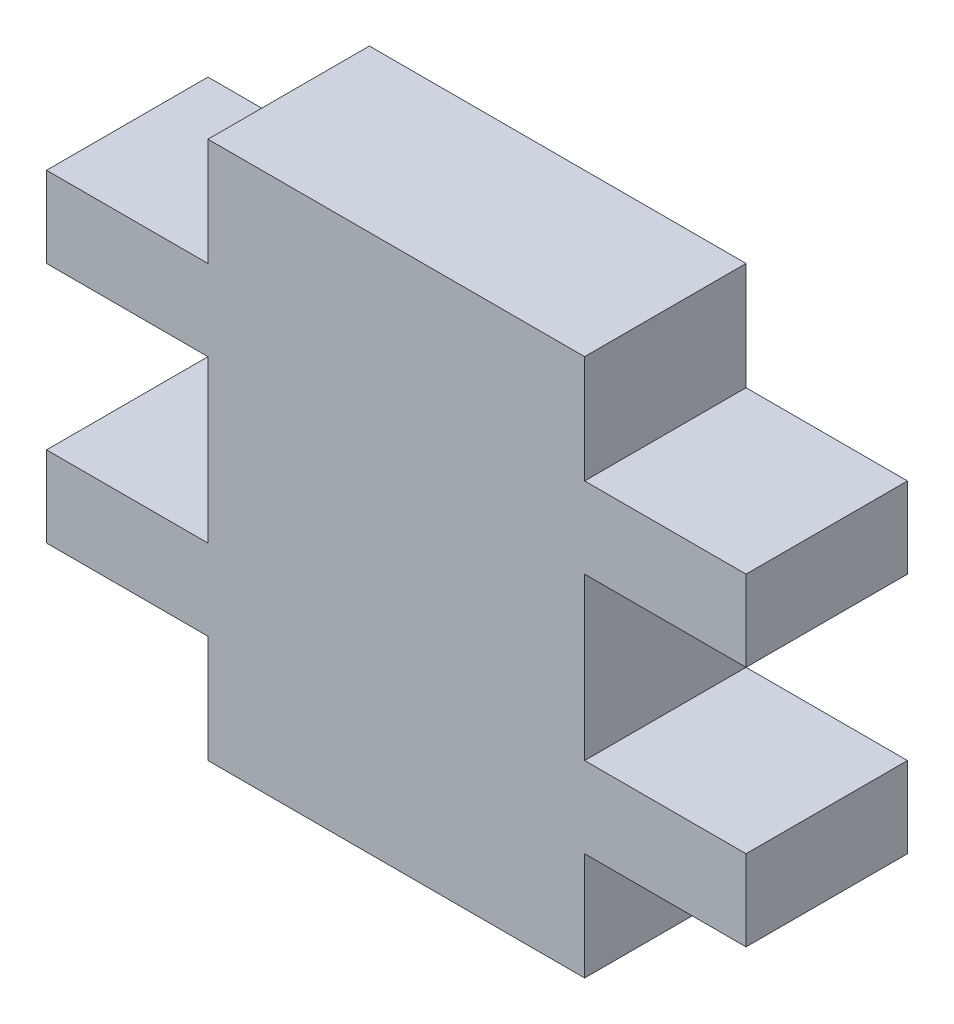
SolidWorks part; units mm, degrees
ref_plane "Plan de face" through (0, 0, 0) normal (0, 0, 1) x (1, 0, 0)
ref_plane "Plan de dessus" through (0, 0, 0) normal (0, 1, 0) x (1, 0, 0)
ref_plane "Plan de droite" through (0, 0, 0) normal (1, 0, 0) x (0, 0, -1)
sketch "Sketch1" plane through (0, 0, 0) normal (0, 0, 1) x (1, 0, 0)
  line L1 (-6.5, -5) -> (6.5, -5)
  line L2 (-6.5, -5) -> (-6.5, 5)
  line L3 (-6.5, 5) -> (6.5, 5)
  line L4 (6.5, -5) -> (6.5, 5)
  line L5 (-6.5, -5) -> (6.5, 5) construction
  line L6 (-6.5, 5) -> (6.5, -5) construction
  point P0 (0, 0)
  dimension "D1" = 13
  dimension "D2" = 10
extrude "Boss-Extrude1" add sketch "Sketch1" along normal blind 3
sketch "Sketch2" plane through (0, 0, 3) normal (0, 0, 1) x (1, 0, 0)
  line L0 (-6.5, 5) -> (-6.5, -5) construction
  line L1 (-6.5, 3) -> (-3.5, 3)
  line L2 (-6.5, 3) -> (-6.5, 5)
  line L3 (-6.5, 5) -> (-3.5, 5)
  line L4 (-3.5, 3) -> (-3.5, 5)
  line L5 (6.5, 5) -> (-6.5, 5) construction
  line L7 (-6.5, 1.5) -> (-3.5, 1.5)
  line L8 (-6.5, 1.5) -> (-6.5, -1.5)
  line L9 (-6.5, -1.5) -> (-3.5, -1.5)
  line L10 (-3.5, 1.5) -> (-3.5, -1.5)
  line L11 (-6.5, -3) -> (-3.5, -3)
  line L12 (-6.5, -3) -> (-6.5, -5)
  line L13 (-6.5, -5) -> (-3.5, -5)
  line L14 (-3.5, -3) -> (-3.5, -5)
  dimension "D1" = 2
  dimension "D2" = 3
  dimension "D3" = 1.5
  dimension "D4" = 3
  dimension "D5" = 3
  dimension "D6" = 3
  dimension "D7" = 2
  dimension "D8" = 1.5
extrude "Cut-Extrude1" cut sketch "Sketch2" against normal blind 3
sketch "Sketch3" plane through (0, 0, 3) normal (0, 0, 1) x (1, 0, 0)
  line L0 (6.5, 5) -> (-3.5, 5) construction
  line L1 (3.5, 5) -> (6.5, 5)
  line L2 (3.5, 5) -> (3.5, 3)
  line L3 (3.5, 3) -> (6.5, 3)
  line L4 (6.5, 5) -> (6.5, 3)
  line L5 (6.5, -5) -> (6.5, 5) construction
  line L7 (6.5, 1.5) -> (3.5, 1.5)
  line L8 (6.5, 1.5) -> (6.5, -1.5)
  line L9 (6.5, -1.5) -> (3.5, -1.5)
  line L10 (3.5, 1.5) -> (3.5, -1.5)
  line L11 (6.5, -3) -> (3.5, -3)
  line L12 (6.5, -3) -> (6.5, -5)
  line L13 (6.5, -5) -> (3.5, -5)
  line L14 (3.5, -3) -> (3.5, -5)
  point P16 (5, -3)
  dimension "D1" = 2
  dimension "D2" = 3
  dimension "D3" = 1.5
  dimension "D4" = 3
  dimension "D5" = 3
  dimension "D6" = 1.5
  dimension "D7" = 2
  dimension "D8" = 3
extrude "Cut-Extrude2" cut sketch "Sketch3" against normal blind 3
